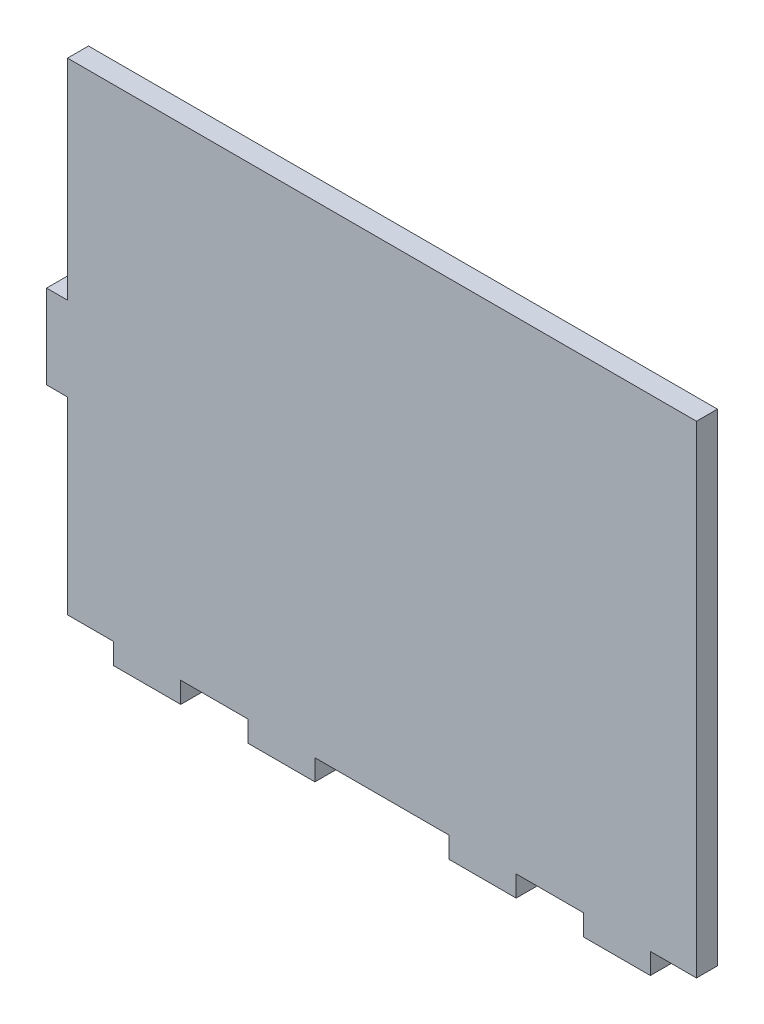
SolidWorks part; units mm, degrees
material "Beech"
ref_plane "Front" through (0, 0, 0) normal (0, 0, 1) x (1, 0, 0)
ref_plane "Top" through (0, 0, 0) normal (0, 1, 0) x (1, 0, 0)
ref_plane "Right" through (0, 0, 0) normal (1, 0, 0) x (0, 0, -1)
sketch "Sketch1" plane through (0, 0, 0) normal (0, 0, 1) x (1, 0, 0)
  line L0 (-40, 28.75) -> (0, 28.75) construction
  line L1 (0, 0) -> (-40, 0) construction
  line L2 (0, 0) -> (0, 33.75) construction
  line L3 (0, 33.75) -> (-40, 33.75) construction
  line L4 (-40, 0) -> (-40, 33.75) construction
  line L5 (0, 0) -> (-40, 33.75) construction
  line L6 (0, 33.75) -> (-40, 0) construction
  line L7 (-40, -28.75) -> (-40, 28.75) construction
  line L8 (-40, 28.75) -> (-32, 28.75) construction
  line L17 (-8, -28.75) -> (8, -28.75)
  line L18 (-8, -31.25) -> (-8, -28.75)
  line L19 (-16, -31.25) -> (-8, -31.25)
  line L20 (-16, -28.75) -> (-16, -31.25)
  line L21 (-24, -28.75) -> (-16, -28.75)
  line L22 (-24, -31.25) -> (-24, -28.75)
  line L23 (-32, -31.25) -> (-24, -31.25)
  line L24 (-32, -28.75) -> (-32, -31.25)
  line L25 (-40, -28.75) -> (-32, -28.75)
  line L26 (8, -31.25) -> (8, -28.75)
  line L27 (16, -31.25) -> (8, -31.25)
  line L28 (16, -28.75) -> (16, -31.25)
  line L29 (24, -28.75) -> (16, -28.75)
  line L30 (24, -31.25) -> (24, -28.75)
  line L31 (32, -31.25) -> (24, -31.25)
  line L32 (32, -28.75) -> (32, -31.25)
  line L33 (40, -28.75) -> (32, -28.75)
  line L34 (40, -28.75) -> (40, 28.75) construction
  line L35 (40, 28.75) -> (32, 28.75) construction
  line L36 (40, 28.75) -> (-40, 28.75)
  line L37 (-37.5, -28.75) -> (-37.5, 28.75) construction
  line L40 (-37.5, -6.25) -> (-40, -6.25)
  line L42 (-40, 3.75) -> (-37.5, 3.75)
  line L48 (-37.5, 28.75) -> (-37.5, 3.75)
  line L49 (-40, 3.75) -> (-40, -6.25)
  line L50 (-37.5, -6.25) -> (-37.5, -28.75)
  line L51 (37.5, -28.75) -> (37.5, 28.75)
  point P4 (-20, 16.875)
  point P28 (0, -28.75)
  dimension "D1" = 5
  dimension "D2" = 33.75
  dimension "D3" = 40
  dimension "D4" = 2.5
  dimension "D5" = 2.5
  dimension "D6" = 10
  dimension "D7" = 25
extrude "Boss-Extrude1" add sketch "Sketch1" along normal blind 2.5 contours L33 L51 L36 L48 L42 L49 L40 L50 L25 L24 L23 L22 L21 L20 L19 L18 L17 L26 L27 L28 L29 L30 L31 L32
sketch "Sketch2" plane through (0, 0, 0) normal (0, 0, 1) x (1, 0, 0)
  line L0 (-33.7768, -20.25) -> (-8.7768, -20.25) construction
  line L1 (-33.7768, -23.75) -> (-8.7768, -23.75) construction
  line L2 (-8, -28.75) -> (8, -28.75) construction
  text T0 "OPPOSITE\r\n" font "Century Gothic" height 3.5
  text T1 "Made In Egypt" font "Century Gothic" height 2
  point P7 (-18.9439, -20.25)
  point P8 (0, 0)
  point P9 (0, 0)
  point P10 (0, 0)
  point P11 (-33.7768, -20.25)
  dimension "D1" = 3.5
  dimension "D2" = 5
  dimension "D4" = 25
extrude "Cut-Extrude1" cut sketch "Sketch2" along normal blind 1
